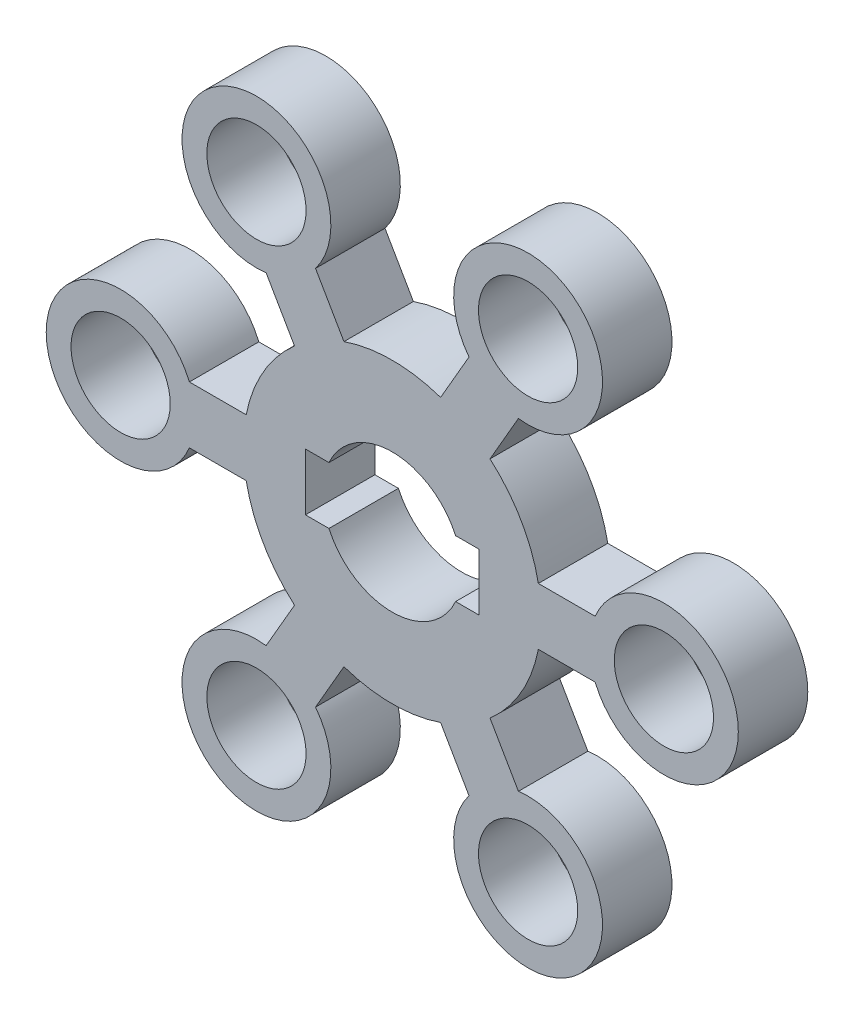
SolidWorks part; units mm, degrees
ref_plane "Front Plane" through (0, 0, 0) normal (0, 0, 1) x (1, 0, 0)
ref_plane "Top Plane" through (0, 0, 0) normal (0, 1, 0) x (1, 0, 0)
ref_plane "Right Plane" through (0, 0, 0) normal (1, 0, 0) x (0, 0, -1)
sketch "Sketch1" plane through (0, 0, 0) normal (0, 0, 1) x (1, 0, 0)
  line L0 (0, 0) -> (0, -1327.7332) construction
  line L1 (0, 0) -> (-1327.7332, 0) construction
  line L2 (58.8876, 11.5) -> (81.7917, 11.5)
  line L3 (81.7917, -11.5) -> (58.8876, -11.5)
  line L4 (39.4031, -45.2482) -> (50.8551, -65.0837)
  line L5 (30.9366, -76.5837) -> (19.4845, -56.7482)
  line L6 (-19.4845, -56.7482) -> (-30.9366, -76.5837)
  line L7 (-50.8551, -65.0837) -> (-39.4031, -45.2482)
  line L8 (-58.8876, -11.5) -> (-81.7917, -11.5)
  line L9 (-81.7917, 11.5) -> (-58.8876, 11.5)
  line L10 (-39.4031, 45.2482) -> (-50.8551, 65.0837)
  line L11 (-30.9366, 76.5837) -> (-19.4845, 56.7482)
  line L12 (19.4845, 56.7482) -> (30.9366, 76.5837)
  line L13 (50.8551, 65.0837) -> (39.4031, 45.2482)
  line L14 (-25.5294, 11.5) -> (-35, 11.5)
  line L15 (-35, 11.5) -> (-35, -11.5)
  line L16 (-35, -11.5) -> (-25.5294, -11.5)
  line L17 (35, -11.5) -> (25.5294, -11.5)
  line L18 (35, 11.5) -> (35, -11.5)
  line L19 (25.5294, 11.5) -> (35, 11.5)
  circle A0 centre (0, 0) radius 109.5 construction
  arc A1 (58.8876, 11.5) -> (39.4031, 45.2482) centre (0, 0) ccw
  arc A2 (-25.5294, -11.5) -> (25.5294, -11.5) centre (0, 0) ccw
  arc A3 (81.7917, -11.5) -> (81.7917, 11.5) centre (109.5, 0) ccw
  circle A4 centre (109.5, 0) radius 20
  arc A5 (30.9366, -76.5837) -> (50.8551, -65.0837) centre (54.75, -94.8298) ccw
  circle A6 centre (54.75, -94.8298) radius 20
  arc A7 (-50.8551, -65.0837) -> (-30.9366, -76.5837) centre (-54.75, -94.8298) ccw
  circle A8 centre (-54.75, -94.8298) radius 20
  arc A9 (-81.7917, 11.5) -> (-81.7917, -11.5) centre (-109.5, 0) ccw
  circle A10 centre (-109.5, 0) radius 20
  arc A11 (-30.9366, 76.5837) -> (-50.8551, 65.0837) centre (-54.75, 94.8298) ccw
  circle A12 centre (-54.75, 94.8298) radius 20
  arc A13 (50.8551, 65.0837) -> (30.9366, 76.5837) centre (54.75, 94.8298) ccw
  circle A14 centre (54.75, 94.8298) radius 20
  arc A15 (39.4031, -45.2482) -> (58.8876, -11.5) centre (0, 0) ccw
  arc A16 (-19.4845, -56.7482) -> (19.4845, -56.7482) centre (0, 0) ccw
  arc A17 (-39.4031, 45.2482) -> (-58.8876, 11.5) centre (0, 0) ccw
  arc A18 (19.4845, 56.7482) -> (-19.4845, 56.7482) centre (0, 0) ccw
  arc A19 (-58.8876, -11.5) -> (-39.4031, -45.2482) centre (0, 0) ccw
  arc A20 (25.5294, 11.5) -> (-25.5294, 11.5) centre (0, 0) ccw
  point P47 (0, 0)
  dimension "D1" = 219
  dimension "D2" = 120
  dimension "D3" = 56
  dimension "D4" = 60
  dimension "D5" = 40
  dimension "D6" = 23
  dimension "D8" = 35
  dimension "D7" = 6
extrude "Boss-Extrude1" add sketch "Sketch1" along normal mid plane 28
